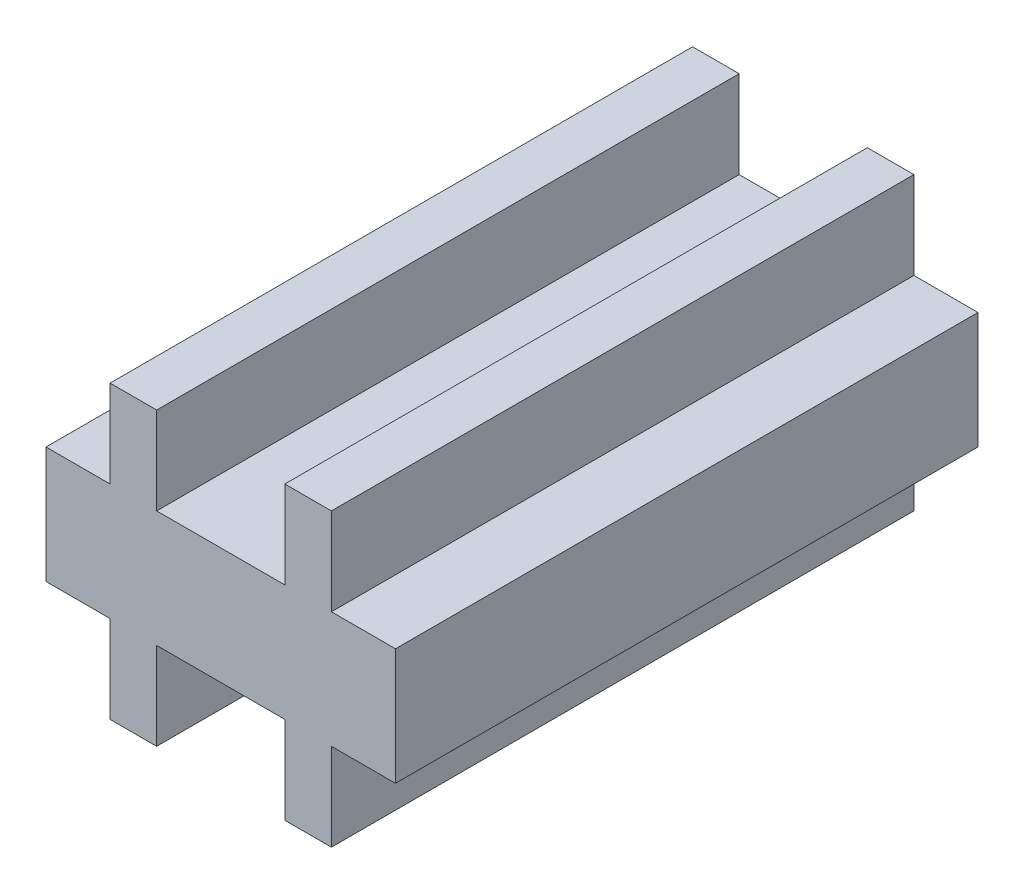
SolidWorks part; units mm, degrees
ref_plane "Спереди" through (0, 0, 0) normal (0, 0, 1) x (1, 0, 0)
ref_plane "Сверху" through (0, 0, 0) normal (0, 1, 0) x (1, 0, 0)
ref_plane "Справа" through (0, 0, 0) normal (1, 0, 0) x (0, 0, -1)
sketch "Эскиз1" plane through (0, 0, 0) normal (0, 0, 1) x (1, 0, 0)
  line L1 (-15, -25) -> (15, -25)
  line L2 (-15, -25) -> (-15, 25)
  line L3 (-15, 25) -> (15, 25)
  line L4 (15, -25) -> (15, 25)
  line L5 (-15, -25) -> (15, 25) construction
  line L6 (-15, 25) -> (15, -25) construction
  line L7 (-4, -25) -> (4, -25)
  line L8 (-4, -25) -> (-4, 25)
  line L9 (-4, 25) -> (4, 25)
  line L10 (4, -25) -> (4, 25)
  line L11 (-4, -25) -> (4, 25) construction
  line L12 (-4, 25) -> (4, -25) construction
  line L13 (-15, -10) -> (15, -10)
  line L14 (-15, -10) -> (-15, 10)
  line L15 (-15, 10) -> (15, 10)
  line L16 (15, -10) -> (15, 10)
  line L17 (-15, -10) -> (15, 10) construction
  line L18 (-15, 10) -> (15, -10) construction
  point P0 (0, 0)
  point P6 (0, 0)
  point P11 (0, 0)
  dimension "D1" = 50
  dimension "D2" = 30
  dimension "D3" = 8
  dimension "D4" = 20
extrude "Бобышка-Вытянуть1" add sketch "Эскиз1" along normal blind 100 contours L15 L10 L13 L4 | L15 L8 L13 L10 | L15 L2 L13 L8 | L8 L15 L10 L3 | L13 L8 L1 L10
mirror "Зеркальное отражение1" about plane through (-15, 0, 100) normal (-1, 0, 0) of "Бобышка-Вытянуть1"
